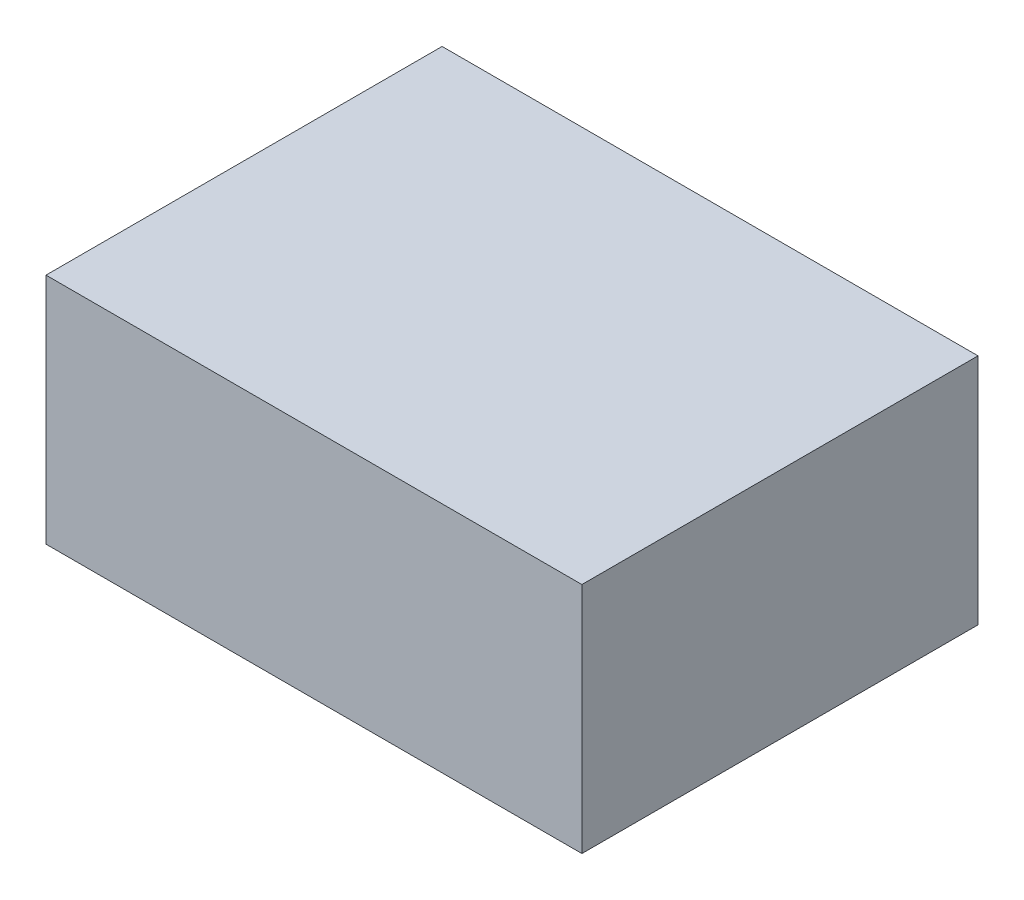
SolidWorks part; units mm, degrees
ref_plane "Front Plane" through (0, 0, 0) normal (0, 0, 1) x (1, 0, 0)
ref_plane "Top Plane" through (0, 0, 0) normal (0, 1, 0) x (1, 0, 0)
ref_plane "Right Plane" through (0, 0, 0) normal (1, 0, 0) x (0, 0, -1)
sketch "Sketch1" plane through (0, 0, 0) normal (0, 1, 0) x (1, 0, 0)
  line L1 (-115, -85) -> (115, -85)
  line L2 (-115, -85) -> (-115, 85)
  line L3 (-115, 85) -> (115, 85)
  line L4 (115, -85) -> (115, 85)
  line L5 (-115, -85) -> (115, 85) construction
  line L6 (-115, 85) -> (115, -85) construction
  point P0 (0, 0)
  dimension "D1" = 230
  dimension "170" = 170
extrude "Boss-Extrude1" add sketch "Sketch1" along normal blind 100
